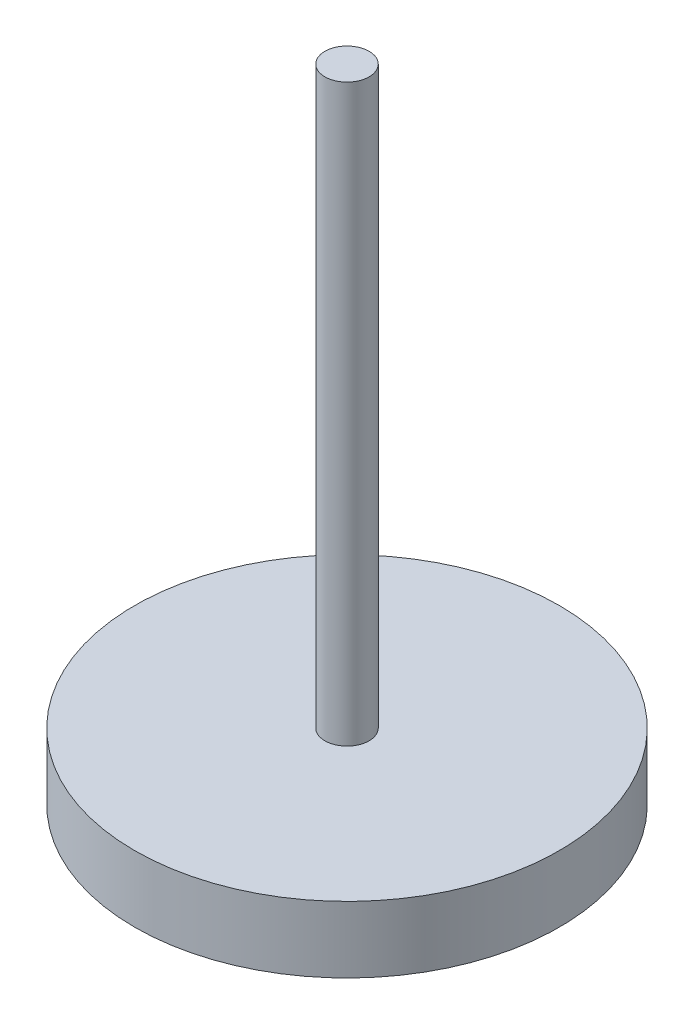
SolidWorks part; units mm, degrees
ref_plane "Front Plane" through (0, 0, 0) normal (0, 0, 1) x (1, 0, 0)
ref_plane "Top Plane" through (0, 0, 0) normal (0, 1, 0) x (1, 0, 0)
ref_plane "Right Plane" through (0, 0, 0) normal (1, 0, 0) x (0, 0, -1)
sketch "Sketch2" plane through (0, 0, 0) normal (0, 1, 0) x (1, 0, 0)
  circle A0 centre (0, 0) radius 48
extrude "Boss-Extrude1" add sketch "Sketch2" along normal blind 15
sketch "Sketch3" plane through (0, 15, 0) normal (0, 1, 0) x (1, 0, 0)
  circle A0 centre (0, 0) radius 5
extrude "Boss-Extrude2" add sketch "Sketch3" along normal blind 130
